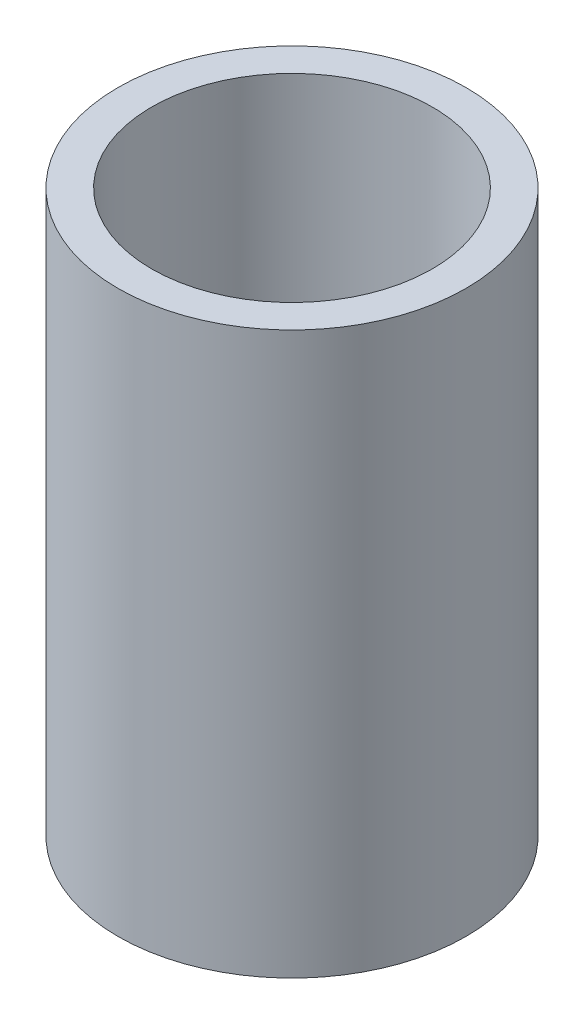
SolidWorks part; units mm, degrees
ref_plane "Front Plane" through (0, 0, 0) normal (0, 0, 1) x (1, 0, 0)
ref_plane "Top Plane" through (0, 0, 0) normal (0, 1, 0) x (1, 0, 0)
ref_plane "Right Plane" through (0, 0, 0) normal (1, 0, 0) x (0, 0, -1)
sketch "Sketch1" plane through (0, 0, 0) normal (0, 1, 0) x (1, 0, 0)
  circle A0 centre (0, 0) radius 12.7
  circle A1 centre (0, 0) radius 15.748
  dimension "D1" = 25.4
  dimension "D2" = 3.048
extrude "Boss-Extrude1" add sketch "Sketch1" along normal blind 50.8
